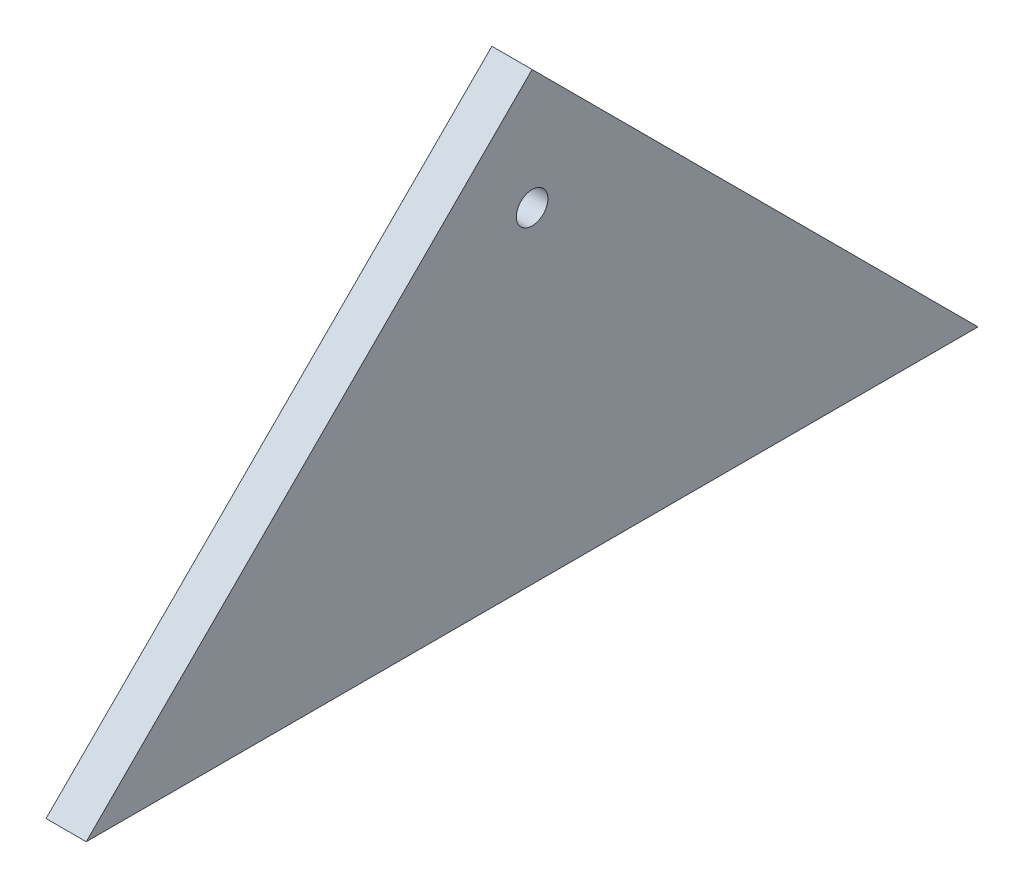
SolidWorks part; units mm, degrees
material "Pine"
ref_plane "Front Plane" through (0, 0, 0) normal (0, 0, 1) x (1, 0, 0)
ref_plane "Top Plane" through (0, 0, 0) normal (0, 1, 0) x (1, 0, 0)
ref_plane "Right Plane" through (0, 0, 0) normal (1, 0, 0) x (0, 0, -1)
sketch "Sketch1" plane through (0, 0, 0) normal (1, 0, 0) x (0, 0, -1)
  line L0 (0, 36.1696) -> (-134.7038, -98.5342)
  line L1 (-134.7038, -98.5342) -> (134.7038, -98.5342)
  line L2 (134.7038, -98.5342) -> (0, 36.1696)
  circle A0 centre (0, 0) radius 4.7625
  dimension "D1" = 9.525
  dimension "D2" = 190.5
  dimension "D3" = 36.1696
extrude "Boss-Extrude1" add sketch "Sketch1" along normal blind 12.1539
